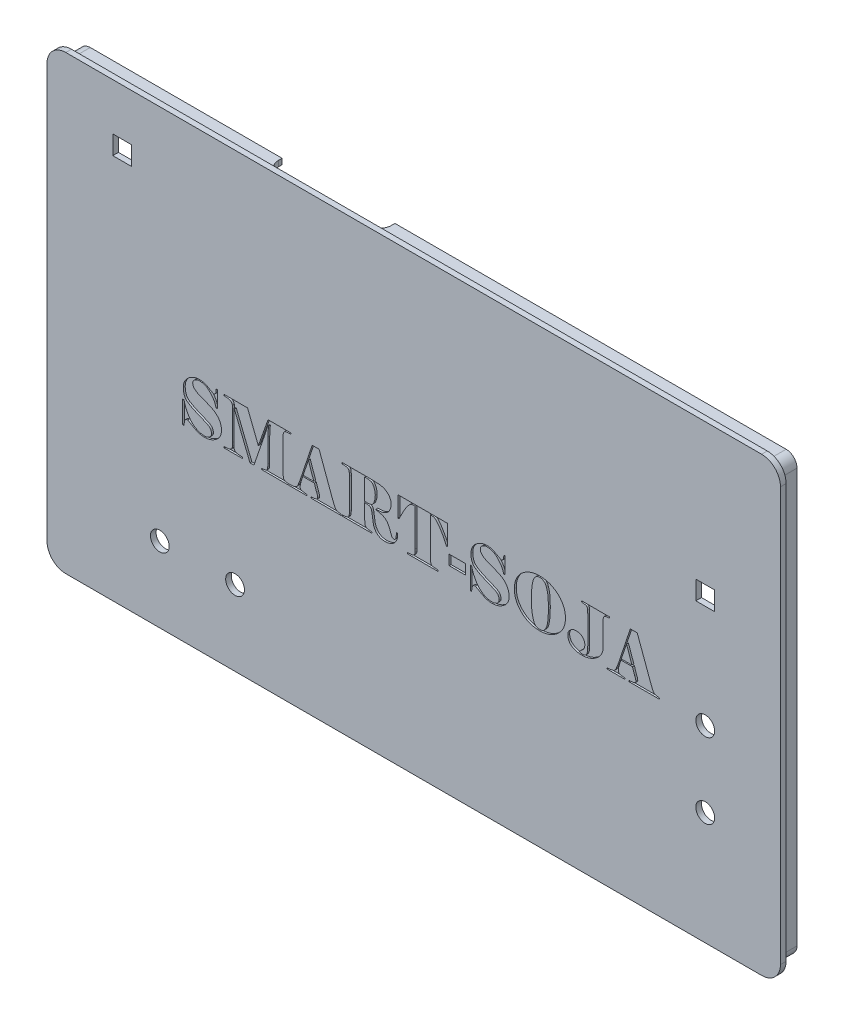
SolidWorks part; units mm, degrees
ref_plane "Plan de face" through (0, 0, 0) normal (0, 0, 1) x (1, 0, 0)
ref_plane "Plan de dessus" through (0, 0, 0) normal (0, 1, 0) x (1, 0, 0)
ref_plane "Plan de droite" through (0, 0, 0) normal (1, 0, 0) x (0, 0, -1)
sketch "Esquisse1" plane through (0, 0, 0) normal (0, 0, 1) x (1, 0, 0)
  line L1 (5, 0) -> (190, 0)
  line L2 (0, 5) -> (0, 115)
  line L3 (5, 120) -> (190, 120)
  line L4 (195, 5) -> (195, 115)
  line L5 (0, 0) -> (195, 120) construction
  line L6 (0, 120) -> (195, 0) construction
  arc A0 (190, 0) -> (195, 5) centre (190, 5) ccw
  arc A1 (0, 115) -> (5, 120) centre (5, 115) cw
  arc A2 (190, 120) -> (195, 115) centre (190, 115) cw
  arc A3 (5, 0) -> (0, 5) centre (5, 5) cw
  point P4 (97.5, 60)
  dimension "D3" = 5
  dimension "D1" = 195
  dimension "D2" = 120
extrude "Boss.-Extru.1" add sketch "Esquisse1" along normal blind 1.5
sketch "Esquisse2" plane through (0, 0, 0) normal (0, 0, -1) x (-1, 0, 0)
  line L8 (-190, 3.6) -> (-5, 3.6)
  line L9 (-3.6, 5) -> (-3.6, 115)
  line L10 (-5, 116.4) -> (-190, 116.4)
  line L11 (-191.4, 115) -> (-191.4, 5)
  line L12 (-190, 2.1) -> (-5, 2.1)
  line L13 (-2.1, 5) -> (-2.1, 115)
  line L14 (-5, 117.9) -> (-190, 117.9)
  line L15 (-192.9, 115) -> (-192.9, 5)
  line L16 (-190, 2.1) -> (-5, 2.1)
  line L17 (-2.1, 5) -> (-2.1, 115)
  line L18 (-5, 117.9) -> (-190, 117.9)
  line L19 (-192.9, 115) -> (-192.9, 5)
  arc A8 (-191.4, 5) -> (-190, 3.6) centre (-190, 5) ccw
  arc A9 (-5, 3.6) -> (-3.6, 5) centre (-5, 5) ccw
  arc A10 (-3.6, 115) -> (-5, 116.4) centre (-5, 115) ccw
  arc A11 (-190, 116.4) -> (-191.4, 115) centre (-190, 115) ccw
  arc A12 (-192.9, 5) -> (-190, 2.1) centre (-190, 5) ccw
  arc A13 (-5, 2.1) -> (-2.1, 5) centre (-5, 5) ccw
  arc A14 (-2.1, 115) -> (-5, 117.9) centre (-5, 115) ccw
  arc A15 (-190, 117.9) -> (-192.9, 115) centre (-190, 115) ccw
  arc A16 (-192.9, 5) -> (-190, 2.1) centre (-190, 5) ccw
  arc A17 (-5, 2.1) -> (-2.1, 5) centre (-5, 5) ccw
  arc A18 (-2.1, 115) -> (-5, 117.9) centre (-5, 115) ccw
  arc A19 (-190, 117.9) -> (-192.9, 115) centre (-190, 115) ccw
  dimension "D1" = 2.1
  dimension "D2" = 1.5
extrude "Boss.-Extru.2" add sketch "Esquisse2" along normal blind 5
sketch "Esquisse3" plane through (0, 117.9, 0) normal (0, 1, 0) x (1, 0, 0)
  line L0 (5, 5) -> (190, 5) construction
  line L1 (56, 5) -> (86, 5)
  line L2 (56, 5) -> (56, 4)
  line L3 (59, 1) -> (83, 1)
  line L4 (86, 5) -> (86, 4)
  line L5 (56, 5) -> (86, 1) construction
  line L6 (56, 1) -> (86, 5) construction
  line L7 (56, 7) -> (56, 4) construction
  arc A0 (83, 1) -> (86, 4) centre (83, 4) ccw
  arc A1 (56, 4) -> (59, 1) centre (59, 4) ccw
  point P4 (71, 3)
  dimension "D1" = 3
  dimension "D2" = 4
  dimension "D3" = 30
extrude "Enlèv. mat.-Extru.1" cut sketch "Esquisse3" against normal blind 5
sketch "Esquisse4" plane through (0, 0, 1.5) normal (0, 0, 1) x (1, 0, 0)
  line L3 (195, 5) -> (195, 115) construction
  line L4 (5, 0) -> (190, 0) construction
  line L5 (0, 115) -> (0, 5) construction
  circle A4 centre (30, 20) radius 2.5
  circle A5 centre (50, 20) radius 2.5
  circle A6 centre (175, 50) radius 2.5
  circle A7 centre (175, 30) radius 2.5
  point P4 (0, 0)
  point P13 (0, 0)
  dimension "D1" = 20
  dimension "D3" = 5
  dimension "D8" = 5
  dimension "D2" = 30
  dimension "D4" = 20
  dimension "D5" = 20
  dimension "D6" = 30
  dimension "D7" = 20
extrude "Enlèv. mat.-Extru.2" cut sketch "Esquisse4" against normal blind 5
sketch "Esquisse5" plane through (0, 0, 1.5) normal (0, 0, 1) x (1, 0, 0)
  line L0 (195, 5) -> (195, 115) construction
  line L1 (172.5, 82.5) -> (177.5, 82.5)
  line L2 (172.5, 82.5) -> (172.5, 77.5)
  line L3 (172.5, 77.5) -> (177.5, 77.5)
  line L4 (177.5, 82.5) -> (177.5, 77.5)
  line L5 (172.5, 82.5) -> (177.5, 77.5) construction
  line L6 (172.5, 77.5) -> (177.5, 82.5) construction
  line L11 (17.5, 107.5) -> (22.5, 107.5)
  line L12 (17.5, 107.5) -> (17.5, 102.5)
  line L13 (17.5, 102.5) -> (22.5, 102.5)
  line L14 (22.5, 107.5) -> (22.5, 102.5)
  line L15 (17.5, 107.5) -> (22.5, 102.5) construction
  line L16 (17.5, 102.5) -> (22.5, 107.5) construction
  line L17 (190, 120) -> (5, 120) construction
  line L18 (0, 115) -> (0, 5) construction
  point P4 (175, 80)
  point P9 (20, 105)
  dimension "D1" = 5
  dimension "D2" = 20
  dimension "D3" = 40
  dimension "D4" = 5
  dimension "D5" = 20
  dimension "D6" = 15
extrude "Enlèv. mat.-Extru.3" cut sketch "Esquisse5" against normal blind 5
sketch "Esquisse6" plane through (0, 0, 1.5) normal (0, 0, 1) x (1, 0, 0)
  line L0 (5, 0) -> (190, 0) construction
  line L2 (0, 115) -> (0, 5) construction
  text T0 "SMART-SOJA" font "Elephant" height in points 48
  dimension "D1" = 50
  dimension "D2" = 35
extrude "Enlèv. mat.-Extru.4" cut sketch "Esquisse6" against normal blind 0.5
